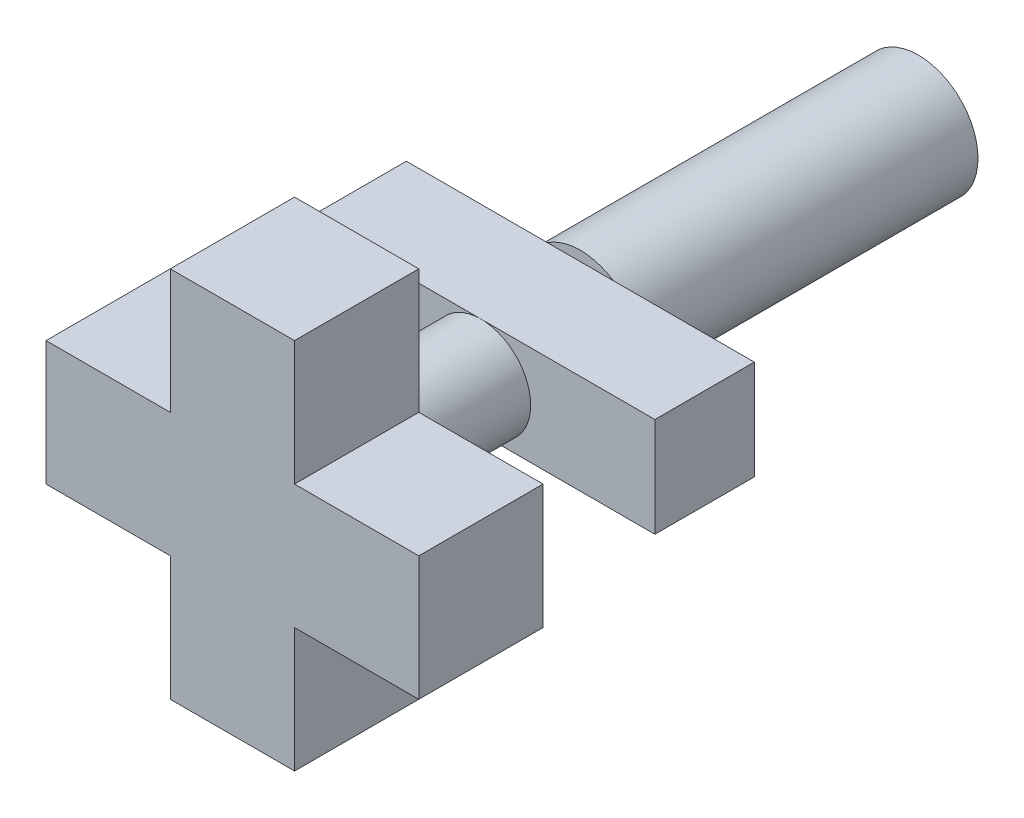
SolidWorks part; units mm, degrees
ref_plane "Front Plane" through (0, 0, 0) normal (0, 0, 1) x (1, 0, 0)
ref_plane "Top Plane" through (0, 0, 0) normal (0, 1, 0) x (1, 0, 0)
ref_plane "Right Plane" through (0, 0, 0) normal (1, 0, 0) x (0, 0, -1)
sketch "Sketch2" plane through (0, 0, 0) normal (0, 0, 1) x (1, 0, 0)
  circle A0 centre (0, 0) radius 3.048
  dimension "D1" = 6.096
extrude "Boss-Extrude1" add sketch "Sketch2" along normal blind 17.272
sketch "Sketch3" plane through (0, 0, 17.272) normal (0, 0, 1) x (1, 0, 0)
  line L1 (-8.89, -2.54) -> (8.89, -2.54)
  line L2 (-8.89, -2.54) -> (-8.89, 2.54)
  line L3 (-8.89, 2.54) -> (8.89, 2.54)
  line L4 (8.89, -2.54) -> (8.89, 2.54)
  line L5 (-8.89, -2.54) -> (8.89, 2.54) construction
  line L6 (-8.89, 2.54) -> (8.89, -2.54) construction
  point P0 (0, 0)
  dimension "D1" = 5.08
  dimension "D2" = 17.78
extrude "Boss-Extrude2" add sketch "Sketch3" along normal blind 5.08
sketch "Sketch4" plane through (0, 0, 22.352) normal (0, 0, 1) x (1, 0, 0)
  circle A0 centre (0, 0) radius 2.54
  dimension "D1" = 5.08
extrude "Boss-Extrude3" add sketch "Sketch4" along normal blind 6.35
sketch "Sketch5" plane through (0, 0, 28.702) normal (0, 0, 1) x (1, 0, 0)
  line L0 (-3.175, 3.175) -> (-3.175, 9.525)
  line L1 (-9.525, -3.175) -> (-3.175, -3.175)
  line L2 (-9.525, -3.175) -> (-9.525, 3.175)
  line L3 (-9.525, 3.175) -> (-3.175, 3.175)
  line L4 (9.525, -3.175) -> (9.525, 3.175)
  line L6 (3.175, -3.175) -> (9.525, -3.175)
  line L7 (-3.175, -9.525) -> (3.175, -9.525)
  line L8 (-3.175, -9.525) -> (-3.175, -3.175)
  line L9 (-3.175, 9.525) -> (3.175, 9.525)
  line L10 (3.175, -9.525) -> (3.175, -3.175)
  line L15 (3.175, 3.175) -> (3.175, 9.525)
  line L16 (3.175, 3.175) -> (9.525, 3.175)
  point P0 (0, 0)
  point P6 (0, 0)
  dimension "D1" = 19.05
  dimension "D2" = 19.05
  dimension "0." = 6.35
  dimension "D3" = 6.35
extrude "Boss-Extrude4" add sketch "Sketch5" along normal blind 6.35
